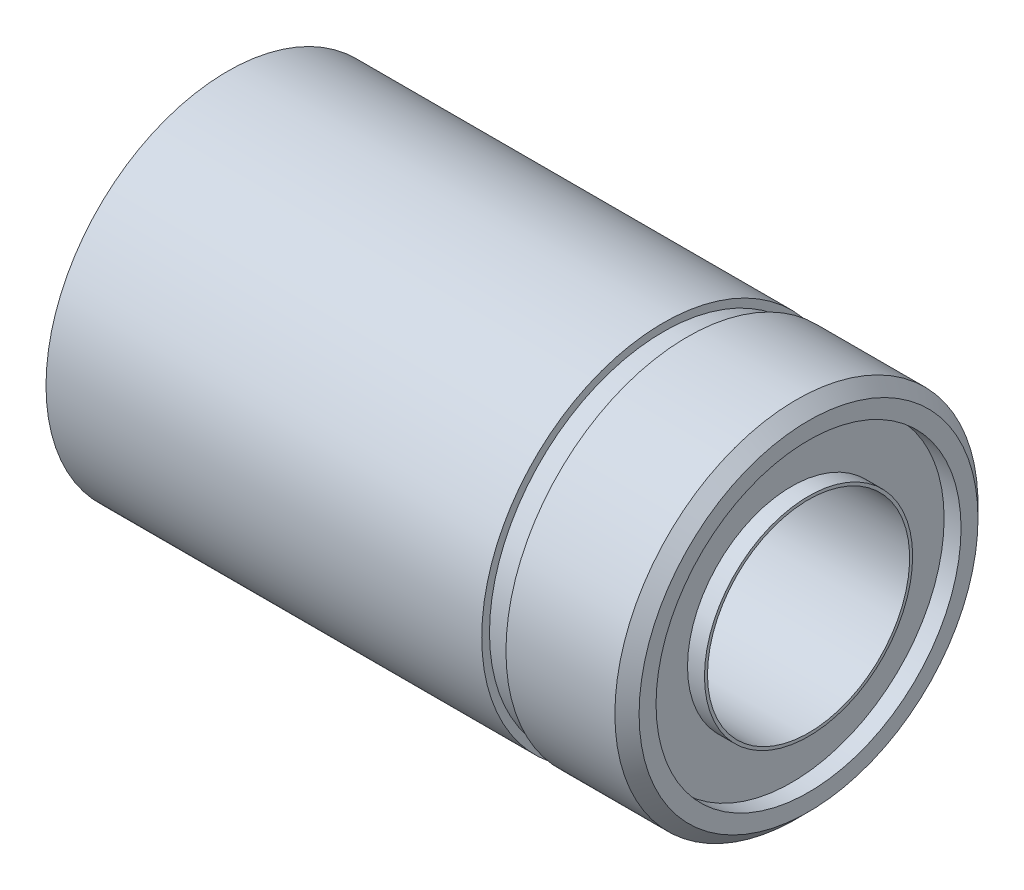
SolidWorks part; units mm, degrees
material "1023 Plech z uhlíkaté oceli (SS)"
ref_plane "Front Plane" through (0, 0, 0) normal (0, 0, 1) x (1, 0, 0)
ref_plane "Top Plane" through (0, 0, 0) normal (0, 1, 0) x (1, 0, 0)
ref_plane "Right Plane" through (0, 0, 0) normal (1, 0, 0) x (0, 0, -1)
sketch "Skica1" plane through (0, 0, 0) normal (0, 0, 1) x (1, 0, 0)
  line L0 (0, 0) -> (22.3333, 0) construction
  line L1 (0, 4.3) -> (0, 4.175)
  line L2 (0, 7.5) -> (5, 7.5)
  line L3 (0, 7.5) -> (0, 6.3)
  line L4 (0, 4.175) -> (45, 4.175)
  line L5 (45, 7.5) -> (45, 6.3)
  line L6 (0, 6.3) -> (0.7, 6.3)
  line L7 (6, 7.5) -> (39, 7.5)
  line L8 (0, 4.3) -> (0.7, 4.3)
  line L9 (0.7, 6.3) -> (0.7, 4.3)
  line L10 (40, 7.5) -> (45, 7.5)
  line L11 (5, 7.5) -> (5, 7.18)
  line L12 (5, 7.18) -> (6, 7.18)
  line L13 (6, 7.5) -> (6, 7.18)
  line L14 (45, 4.3) -> (45, 4.175)
  line L15 (39, 7.5) -> (39, 7.18)
  line L16 (39, 7.18) -> (40, 7.18)
  line L17 (40, 7.5) -> (40, 7.18)
  line L18 (45, 6.3) -> (44.3, 6.3)
  line L20 (45, 4.3) -> (44.3, 4.3)
  line L21 (44.3, 6.3) -> (44.3, 4.3)
  dimension "D1" = 15
  dimension "D2" = 8.35
  dimension "D3" = 12.6
  dimension "D4" = 8.6
  dimension "D5" = 0.7
  dimension "D6" = 45
  dimension "D7" = 5
  dimension "D8" = 5
  dimension "D9" = 1
  dimension "D10" = 0.32
revolve "Rotovat1" add sketch "Skica1" angle 360 about L0
chamfer "Zkosení1" distance 0.5 angle 45 2 edges at (45, 0, 7.5) (0, 0, 7.5)
sketch "草图1" plane through (0, 0, 0) normal (-1, 0, 0) x (0, 0, 1)
  circle A0 centre (0, 0) radius 8.8
extrude "切除-拉伸1" cut sketch "草图1" against normal blind 21
